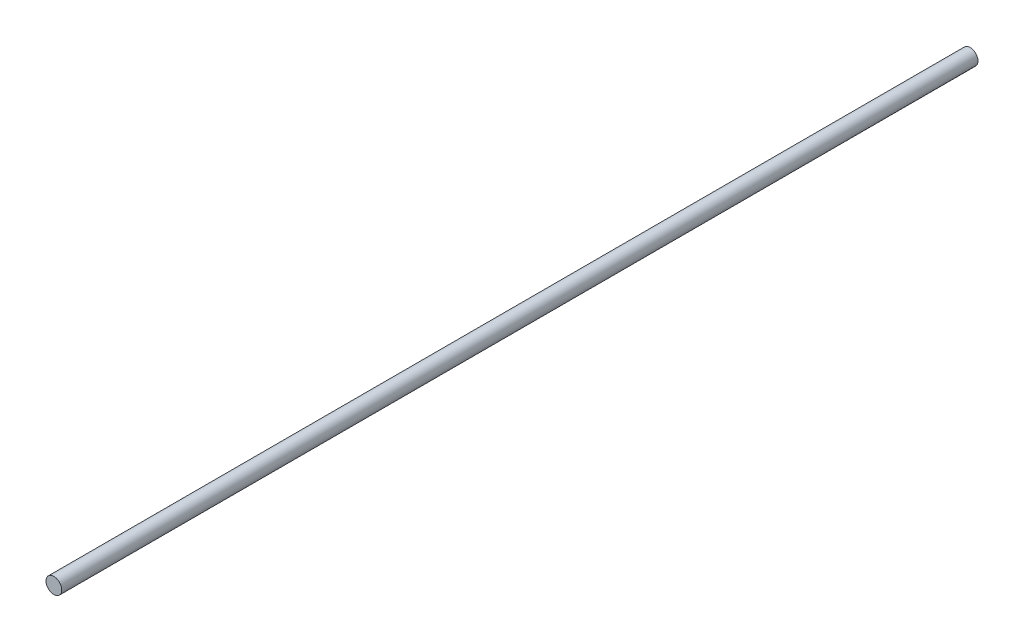
SolidWorks part; units mm, degrees
ref_plane "前视基准面" through (0, 0, 0) normal (0, 0, 1) x (1, 0, 0)
ref_plane "上视基准面" through (0, 0, 0) normal (0, 1, 0) x (1, 0, 0)
ref_plane "右视基准面" through (0, 0, 0) normal (1, 0, 0) x (0, 0, -1)
sketch "草图1" plane through (0, 0, 0) normal (0, 0, 1) x (1, 0, 0)
  circle A0 centre (0, 0) radius 3
  dimension "D1" = 6
extrude "凸台-拉伸1" add sketch "草图1" along normal blind 349.4
